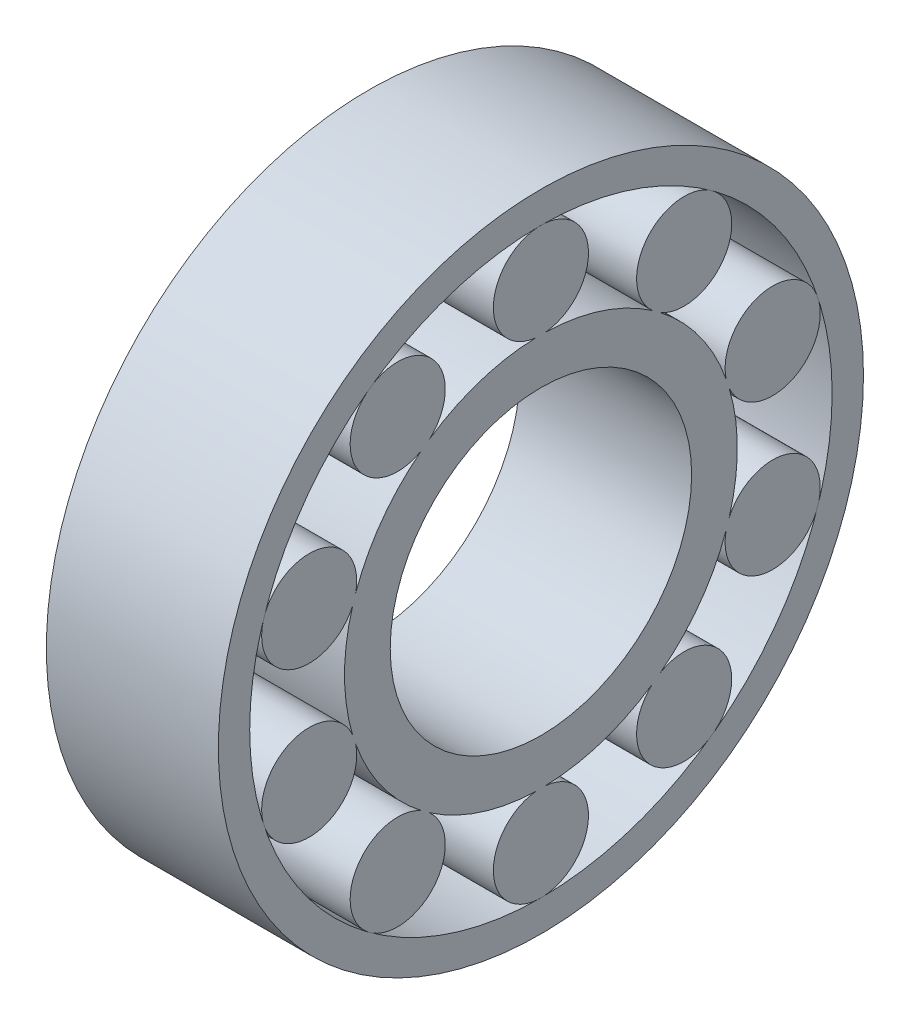
SolidWorks part; units mm, degrees
material "AISI 1020"
ref_plane "Alzado" through (0, 0, 0) normal (0, 0, 1) x (1, 0, 0)
ref_plane "Planta" through (0, 0, 0) normal (0, 1, 0) x (1, 0, 0)
ref_plane "Vista lateral" through (0, 0, 0) normal (1, 0, 0) x (0, 0, -1)
sketch "Croquis1" plane through (0, 0, 0) normal (1, 0, 0) x (0, 0, -1)
  circle A0 centre (0, 0) radius 23.8125
  circle A1 centre (0, 0) radius 11.125
  dimension "D1" = 47.625
  dimension "D2" = 22.25
extrude "Saliente-Extruir1" add sketch "Croquis1" along normal blind 12.7 contours A0 | A1
sketch "Croquis2" plane through (12.7, 0, 0) normal (1, 0, 0) x (0, 0, -1)
  circle A0 centre (0, 0) radius 21.5
  circle A1 centre (0, 0) radius 14.5
  dimension "D1" = 43
  dimension "D2" = 29
extrude "Cortar-Extruir1" cut sketch "Croquis2" against normal blind 12.7
sketch "Croquis3" plane through (12.7, 0, 0) normal (1, 0, 0) x (0, 0, -1)
  circle A0 centre (0, 17.9886) radius 3.5114
  circle A1 centre (10.5734, 14.5531) radius 3.5114
  circle A2 centre (17.1082, 5.5588) radius 3.5114
  circle A3 centre (17.1082, -5.5588) radius 3.5114
  circle A4 centre (10.5734, -14.5531) radius 3.5114
  circle A5 centre (0, -17.9886) radius 3.5114
  circle A6 centre (-10.5734, -14.5531) radius 3.5114
  circle A7 centre (-17.1082, -5.5588) radius 3.5114
  circle A8 centre (-17.1082, 5.5588) radius 3.5114
  circle A9 centre (-10.5734, 14.5531) radius 3.5114
  point P22 (0, 0)
  dimension "D1" = 10
extrude "Saliente-Extruir2" add sketch "Croquis3" against normal blind 12.7
